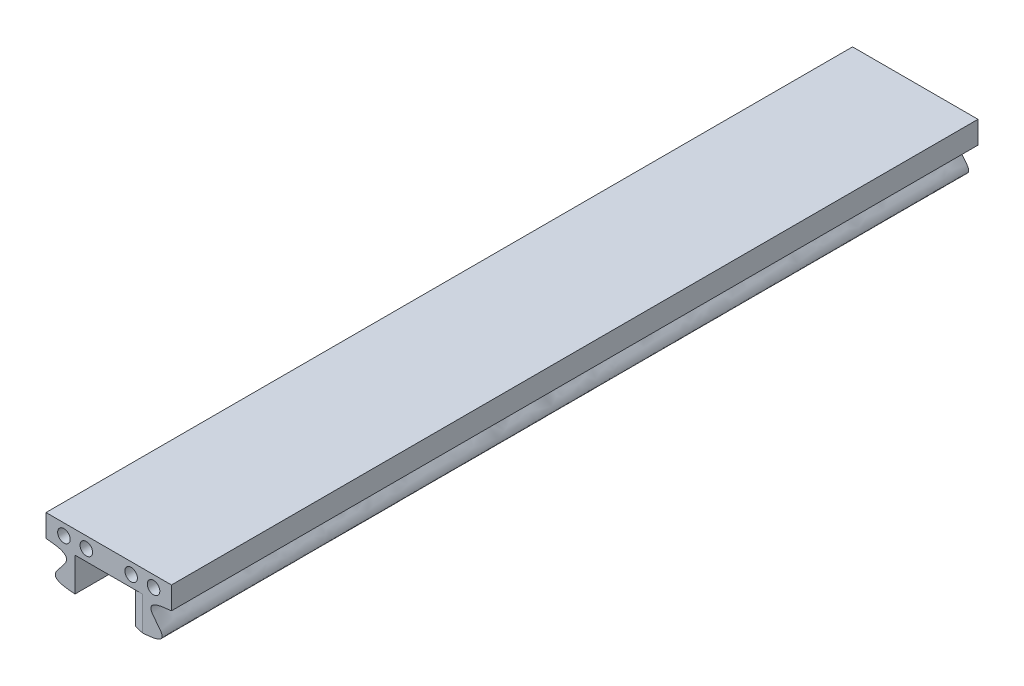
SolidWorks part; units mm, degrees
ref_plane "Front Plane" through (0, 0, 0) normal (0, 0, 1) x (1, 0, 0)
ref_plane "Top Plane" through (0, 0, 0) normal (0, 1, 0) x (1, 0, 0)
ref_plane "Right Plane" through (0, 0, 0) normal (1, 0, 0) x (0, 0, -1)
sketch "Sketch1" plane through (0, 0, 0) normal (0, 0, 1) x (1, 0, 0)
  line L0 (6.5, 7.5) -> (0, 7.5)
  line L1 (0, 0) -> (28, 0)
  line L2 (0, 0) -> (0, 12.5)
  line L3 (0, 12.5) -> (28, 12.5)
  line L4 (28, 0) -> (28, 12.5)
  line L5 (6.5, 0) -> (21.5, 0)
  line L6 (6.5, 0) -> (6.5, 7.5)
  line L7 (6.5, 7.5) -> (21.5, 7.5)
  line L8 (21.5, 0) -> (21.5, 7.5)
  line L9 (21.5, 7.5) -> (28, 7.5)
  line L10 (14, 7.5) -> (14, 0)
  spline S0 degree 3 poles (0, 7.5) (12.3752, 6.6056) (-5.5956, 0.5569) (6.5, 0) knots 0 0 0 0 1 1 1 1
  spline S1 degree 3 poles (28, 7.5) (15.6248, 6.6056) (33.5956, 0.5569) (21.5, 0) knots 0 0 0 0 1 1 1 1
  dimension "D1" = 12.5
  dimension "D2" = 28
  dimension "D3" = 6.5
  dimension "D4" = 6.5
  dimension "D5" = 7.5
extrude "Boss-Extrude1" add sketch "Sketch1" along normal blind 180 contours L7 L9 L4 L3 L2 L0 | L0 S0 L6 | S1 L9 L8
sketch "Sketch3" plane through (0, 7.5, 0) normal (0, -1, 0) x (1, 0, 0)
  line L0 (21.5, 180) -> (19.51, 179.504)
  line L1 (19.51, 179.504) -> (19.51, 178.506)
  line L2 (19.51, 178.506) -> (21.5, 178.008)
  line L3 (21.5, 180) -> (21.5, 0) construction
  line L4 (21.5, 180) -> (21.5, 0) construction
  line L5 (19.51, 176.512) -> (19.51, 175.514)
  line L6 (21.5, 177.008) -> (19.51, 176.512)
  line L7 (19.51, 175.514) -> (21.5, 175.016)
  line L8 (19.51, 173.52) -> (19.51, 172.522)
  line L9 (21.5, 174.016) -> (19.51, 173.52)
  line L10 (19.51, 172.522) -> (21.5, 172.024)
  line L11 (19.51, 170.528) -> (19.51, 169.53)
  line L12 (21.5, 171.024) -> (19.51, 170.528)
  line L13 (19.51, 169.53) -> (21.5, 169.032)
  line L14 (19.51, 167.5359) -> (19.51, 166.538)
  line L15 (21.5, 168.032) -> (19.51, 167.5359)
  line L16 (19.51, 166.538) -> (21.5, 166.04)
  line L17 (19.51, 164.5439) -> (19.51, 163.546)
  line L18 (21.5, 165.04) -> (19.51, 164.5439)
  line L19 (19.51, 163.546) -> (21.5, 163.0479)
  line L20 (19.51, 161.5519) -> (19.51, 160.5539)
  line L21 (21.5, 162.0479) -> (19.51, 161.5519)
  line L22 (19.51, 160.5539) -> (21.5, 160.0559)
  line L23 (19.51, 158.5599) -> (19.51, 157.5619)
  line L24 (21.5, 159.0559) -> (19.51, 158.5599)
  line L25 (19.51, 157.5619) -> (21.5, 157.0639)
  line L26 (19.51, 155.5679) -> (19.51, 154.5699)
  line L27 (21.5, 156.0639) -> (19.51, 155.5679)
  line L28 (19.51, 154.5699) -> (21.5, 154.0719)
  line L29 (19.51, 152.5759) -> (19.51, 151.5779)
  line L30 (21.5, 153.0719) -> (19.51, 152.5759)
  line L31 (19.51, 151.5779) -> (21.5, 151.0799)
  line L32 (19.51, 149.5839) -> (19.51, 148.5859)
  line L33 (21.5, 150.0799) -> (19.51, 149.5839)
  line L34 (19.51, 148.5859) -> (21.5, 148.0879)
  line L35 (19.51, 146.5919) -> (19.51, 145.5939)
  line L36 (21.5, 147.0879) -> (19.51, 146.5919)
  line L37 (19.51, 145.5939) -> (21.5, 145.0959)
  line L38 (19.51, 143.5999) -> (19.51, 142.6019)
  line L39 (21.5, 144.0959) -> (19.51, 143.5999)
  line L40 (19.51, 142.6019) -> (21.5, 142.1039)
  line L41 (19.51, 140.6079) -> (19.51, 139.6099)
  line L42 (21.5, 141.1039) -> (19.51, 140.6079)
  line L43 (19.51, 139.6099) -> (21.5, 139.1119)
  line L44 (19.51, 137.6159) -> (19.51, 136.6179)
  line L45 (21.5, 138.1119) -> (19.51, 137.6159)
  line L46 (19.51, 136.6179) -> (21.5, 136.1199)
  line L47 (19.51, 134.6238) -> (19.51, 133.6258)
  line L48 (21.5, 135.1198) -> (19.51, 134.6238)
  line L49 (19.51, 133.6258) -> (21.5, 133.1278)
  line L50 (19.51, 131.6318) -> (19.51, 130.6338)
  line L51 (21.5, 132.1278) -> (19.51, 131.6318)
  line L52 (19.51, 130.6338) -> (21.5, 130.1358)
  line L53 (19.51, 128.6398) -> (19.51, 127.6418)
  line L54 (21.5, 129.1358) -> (19.51, 128.6398)
  line L55 (19.51, 127.6418) -> (21.5, 127.1438)
  line L56 (19.51, 125.6478) -> (19.51, 124.6498)
  line L57 (21.5, 126.1438) -> (19.51, 125.6478)
  line L58 (19.51, 124.6498) -> (21.5, 124.1518)
  line L59 (19.51, 122.6558) -> (19.51, 121.6578)
  line L60 (21.5, 123.1518) -> (19.51, 122.6558)
  line L61 (19.51, 121.6578) -> (21.5, 121.1598)
  line L62 (19.51, 119.6638) -> (19.51, 118.6658)
  line L63 (21.5, 120.1598) -> (19.51, 119.6638)
  line L64 (19.51, 118.6658) -> (21.5, 118.1678)
  line L65 (19.51, 116.6718) -> (19.51, 115.6738)
  line L66 (21.5, 117.1678) -> (19.51, 116.6718)
  line L67 (19.51, 115.6738) -> (21.5, 115.1758)
  line L68 (19.51, 113.6798) -> (19.51, 112.6818)
  line L69 (21.5, 114.1758) -> (19.51, 113.6798)
  line L70 (19.51, 112.6818) -> (21.5, 112.1838)
  line L71 (19.51, 110.6878) -> (19.51, 109.6898)
  line L72 (21.5, 111.1838) -> (19.51, 110.6878)
  line L73 (19.51, 109.6898) -> (21.5, 109.1918)
  line L74 (19.51, 107.6958) -> (19.51, 106.6978)
  line L75 (21.5, 108.1918) -> (19.51, 107.6958)
  line L76 (19.51, 106.6978) -> (21.5, 106.1998)
  line L77 (19.51, 104.7037) -> (19.51, 103.7057)
  line L78 (21.5, 105.1997) -> (19.51, 104.7037)
  line L79 (19.51, 103.7057) -> (21.5, 103.2077)
  line L80 (19.51, 101.7117) -> (19.51, 100.7137)
  line L81 (21.5, 102.2077) -> (19.51, 101.7117)
  line L82 (19.51, 100.7137) -> (21.5, 100.2157)
  line L83 (19.51, 98.7197) -> (19.51, 97.7217)
  line L84 (21.5, 99.2157) -> (19.51, 98.7197)
  line L85 (19.51, 97.7217) -> (21.5, 97.2237)
  line L86 (19.51, 95.7277) -> (19.51, 94.7297)
  line L87 (21.5, 96.2237) -> (19.51, 95.7277)
  line L88 (19.51, 94.7297) -> (21.5, 94.2317)
  line L89 (19.51, 92.7357) -> (19.51, 91.7377)
  line L90 (21.5, 93.2317) -> (19.51, 92.7357)
  line L91 (19.51, 91.7377) -> (21.5, 91.2397)
  line L92 (19.51, 89.7437) -> (19.51, 88.7457)
  line L93 (21.5, 90.2397) -> (19.51, 89.7437)
  line L94 (19.51, 88.7457) -> (21.5, 88.2477)
  line L95 (19.51, 86.7517) -> (19.51, 85.7537)
  line L96 (21.5, 87.2477) -> (19.51, 86.7517)
  line L97 (19.51, 85.7537) -> (21.5, 85.2557)
  line L98 (19.51, 83.7597) -> (19.51, 82.7617)
  line L99 (21.5, 84.2557) -> (19.51, 83.7597)
  line L100 (19.51, 82.7617) -> (21.5, 82.2637)
  line L101 (19.51, 80.7677) -> (19.51, 79.7697)
  line L102 (21.5, 81.2637) -> (19.51, 80.7677)
  line L103 (19.51, 79.7697) -> (21.5, 79.2717)
  line L104 (19.51, 77.7756) -> (19.51, 76.7777)
  line L105 (21.5, 78.2717) -> (19.51, 77.7756)
  line L106 (19.51, 76.7777) -> (21.5, 76.2797)
  line L107 (19.51, 74.7836) -> (19.51, 73.7857)
  line L108 (21.5, 75.2797) -> (19.51, 74.7836)
  line L109 (19.51, 73.7857) -> (21.5, 73.2876)
  line L110 (19.51, 71.7916) -> (19.51, 70.7936)
  line L111 (21.5, 72.2876) -> (19.51, 71.7916)
  line L112 (19.51, 70.7936) -> (21.5, 70.2956)
  line L113 (19.51, 68.7996) -> (19.51, 67.8016)
  line L114 (21.5, 69.2956) -> (19.51, 68.7996)
  line L115 (19.51, 67.8016) -> (21.5, 67.3036)
  line L116 (19.51, 65.8076) -> (19.51, 64.8096)
  line L117 (21.5, 66.3036) -> (19.51, 65.8076)
  line L118 (19.51, 64.8096) -> (21.5, 64.3116)
  line L119 (19.51, 62.8156) -> (19.51, 61.8176)
  line L120 (21.5, 63.3116) -> (19.51, 62.8156)
  line L121 (19.51, 61.8176) -> (21.5, 61.3196)
  line L122 (19.51, 59.8236) -> (19.51, 58.8256)
  line L123 (21.5, 60.3196) -> (19.51, 59.8236)
  line L124 (19.51, 58.8256) -> (21.5, 58.3276)
  line L125 (19.51, 56.8316) -> (19.51, 55.8336)
  line L126 (21.5, 57.3276) -> (19.51, 56.8316)
  line L127 (19.51, 55.8336) -> (21.5, 55.3356)
  line L128 (19.51, 53.8396) -> (19.51, 52.8416)
  line L129 (21.5, 54.3356) -> (19.51, 53.8396)
  line L130 (19.51, 52.8416) -> (21.5, 52.3436)
  line L131 (19.51, 50.8476) -> (19.51, 49.8496)
  line L132 (21.5, 51.3436) -> (19.51, 50.8476)
  line L133 (19.51, 49.8496) -> (21.5, 49.3516)
  line L134 (19.51, 47.8556) -> (19.51, 46.8576)
  line L135 (21.5, 48.3516) -> (19.51, 47.8556)
  line L136 (19.51, 46.8576) -> (21.5, 46.3596)
  line L137 (21.5, 180) -> (21.5, 46.3596)
  line L138 (21.5, 45.3516) -> (19.51, 44.8556)
  line L139 (19.51, 44.8556) -> (19.51, 43.8576)
  line L140 (19.51, 43.8576) -> (21.5, 43.3596)
  line L141 (21.5, 42.3516) -> (19.51, 41.8556)
  line L142 (19.51, 41.8556) -> (19.51, 40.8576)
  line L143 (19.51, 40.8576) -> (21.5, 40.3596)
  line L144 (21.5, 39.3516) -> (19.51, 38.8556)
  line L145 (19.51, 38.8556) -> (19.51, 37.8576)
  line L146 (19.51, 37.8576) -> (21.5, 37.3596)
  line L147 (21.5, 36.3516) -> (19.51, 35.8556)
  line L148 (19.51, 35.8556) -> (19.51, 34.8576)
  line L149 (19.51, 34.8576) -> (21.5, 34.3596)
  line L150 (21.5, 33.3516) -> (19.51, 32.8556)
  line L151 (19.51, 32.8556) -> (19.51, 31.8576)
  line L152 (19.51, 31.8576) -> (21.5, 31.3596)
  line L153 (21.5, 30.3516) -> (19.51, 29.8556)
  line L154 (19.51, 29.8556) -> (19.51, 28.8576)
  line L155 (19.51, 28.8576) -> (21.5, 28.3596)
  line L156 (21.5, 27.3516) -> (19.51, 26.8556)
  line L157 (19.51, 26.8556) -> (19.51, 25.8576)
  line L158 (19.51, 25.8576) -> (21.5, 25.3596)
  line L159 (21.5, 24.3516) -> (19.51, 23.8556)
  line L160 (19.51, 23.8556) -> (19.51, 22.8576)
  line L161 (19.51, 22.8576) -> (21.5, 22.3596)
  line L162 (21.5, 21.3516) -> (19.51, 20.8556)
  line L163 (19.51, 20.8556) -> (19.51, 19.8576)
  line L164 (19.51, 19.8576) -> (21.5, 19.3596)
  line L165 (21.5, 18.3516) -> (19.51, 17.8556)
  line L166 (19.51, 17.8556) -> (19.51, 16.8576)
  line L167 (19.51, 16.8576) -> (21.5, 16.3596)
  line L168 (21.5, 15.3516) -> (19.51, 14.8556)
  line L169 (19.51, 14.8556) -> (19.51, 13.8576)
  line L170 (19.51, 13.8576) -> (21.5, 13.3596)
  line L171 (21.5, 12.3516) -> (19.51, 11.8556)
  line L172 (19.51, 11.8556) -> (19.51, 10.8576)
  line L173 (19.51, 10.8576) -> (21.5, 10.3596)
  line L174 (21.5, 9.3516) -> (19.51, 8.8556)
  line L175 (19.51, 8.8556) -> (19.51, 7.8576)
  line L176 (19.51, 7.8576) -> (21.5, 7.3596)
  line L177 (21.5, 6.3516) -> (19.51, 5.8556)
  line L178 (19.51, 5.8556) -> (19.51, 4.8576)
  line L179 (19.51, 4.8576) -> (21.5, 4.3596)
  line L180 (21.5, 3.3516) -> (19.51, 2.8556)
  line L181 (19.51, 2.8556) -> (19.51, 1.8576)
  line L182 (19.51, 1.8576) -> (21.5, 1.3596)
  line L183 (21.5, 46.3596) -> (21.5, 1.3596)
  line M2 (21.5, 0) -> (21.5, 180)
  dimension "D1" = 1.99
  dimension "D2" = 0.496
  dimension "D3" = 0.498
  dimension "D4" = 0.998
  dimension "D6" = 1
  dimension "D5" = 45
  dimension "D7" = 16
extrude "Boss-Extrude2" add sketch "Sketch3" along normal up to vertex (7.5 mm away) contours L134 L136 L135 M2 | L131 L133 L132 M2 | L128 L130 L129 M2 | L125 L127 L126 M2 | L122 L124 L123 M2 | L119 L121 L120 M2 | L116 L118 L117 M2 | L113 L115 L114 M2 | L110 L112 L111 M2 | L107 L109 L108 M2 | L104 L106 L105 M2 | L101 L103 L102 M2 | L98 L100 L99 M2 | L95 L97 L96 M2 | L92 L94 L93 M2 | L89 L91 L90 M2 | L86 L88 L87 M2 | L83 L85 L84 M2 | L80 L82 L81 M2 | L77 L79 L78 M2 | L74 L76 L75 M2 | L71 L73 L72 M2 | L68 L70 L69 M2 | L65 L67 L66 M2 | L62 L64 L63 M2 | L59 L61 L60 M2 | L56 L58 L57 M2 | L53 L55 L54 M2 | L50 L52 L51 M2 | L47 L49 L48 M2 | L1 L2 L0 M2 | L44 L46 L45 M2 | L41 L43 L42 M2 | L38 L40 L39 M2 | L35 L37 L36 M2 | L32 L34 L33 M2 | L29 L31 L30 M2 | L26 L28 L27 M2 | L23 L25 L24 M2 | L5 L7 L6 M2 | L8 L10 L9 M2 | L11 L13 L12 M2 | L14 L16 L15 M2 | L17 L19 L18 M2 | L20 L22 L21 M2 | L139 L140 L138 M2 | L181 L182 L180 M2 | L178 L179 L177 M2 | L175 L176 L174 M2 | L172 L173 L171 M2 | L169 L170 L168 M2 | L166 L167 L165 M2 | L163 L164 L162 M2 | L160 L161 L159 M2 | L157 L158 L156 M2 | L154 L155 L153 M2 | L151 L152 L150 M2 | L148 L149 L147 M2 | L145 L146 L144 M2 | L142 L143 L141 M2
sketch "Sketch4" plane through (0, 0, 180) normal (0, 0, 1) x (1, 0, 0)
  line L0 (28, 7.5) -> (28, 12.5) construction
  line L1 (0, 12.5) -> (28, 12.5) construction
  line L2 (14, 7.5) -> (14, 12.5)
  line L3 (6.5, 7.5) -> (21.5, 7.5) construction
  circle A0 centre (24, 10) radius 1.4
  circle A2 centre (19, 10) radius 1.4
  circle A3 centre (9, 10) radius 1.4
  circle A4 centre (4, 10) radius 1.4
  dimension "D1" = 2.8
  dimension "D2" = 2.8
  dimension "D4" = 2.5
  dimension "D3" = 4
  dimension "D5" = 2.5
  dimension "D6" = 5
extrude "Cut-Extrude1" cut sketch "Sketch4" against normal blind 5 contours A0 | A2 | A3 | A4
